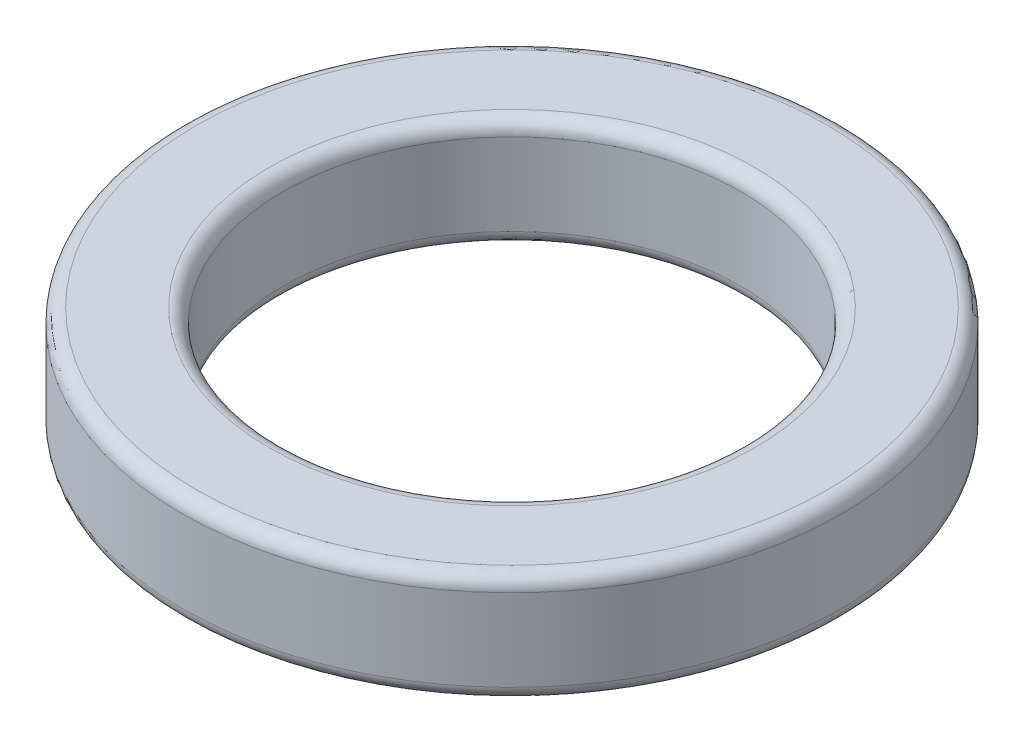
SolidWorks part; units mm, degrees
ref_plane "Front Plane" through (0, 0, 0) normal (0, 0, 1) x (1, 0, 0)
ref_plane "Top Plane" through (0, 0, 0) normal (0, 1, 0) x (1, 0, 0)
ref_plane "Right Plane" through (0, 0, 0) normal (1, 0, 0) x (0, 0, -1)
sketch "Sketch1" plane through (0, 0, 0) normal (0, 1, 0) x (1, 0, 0)
  circle A0 centre (0, 0) radius 36
  circle A1 centre (0, 0) radius 25
extrude "Boss-Extrude1" add sketch "Sketch1" along normal mid plane 12
fillet "Fillet1" radius 1.524 4 edges at (0, -6, 36) (0, -6, 25) (0, 6, 25) (0, 6, 36)
